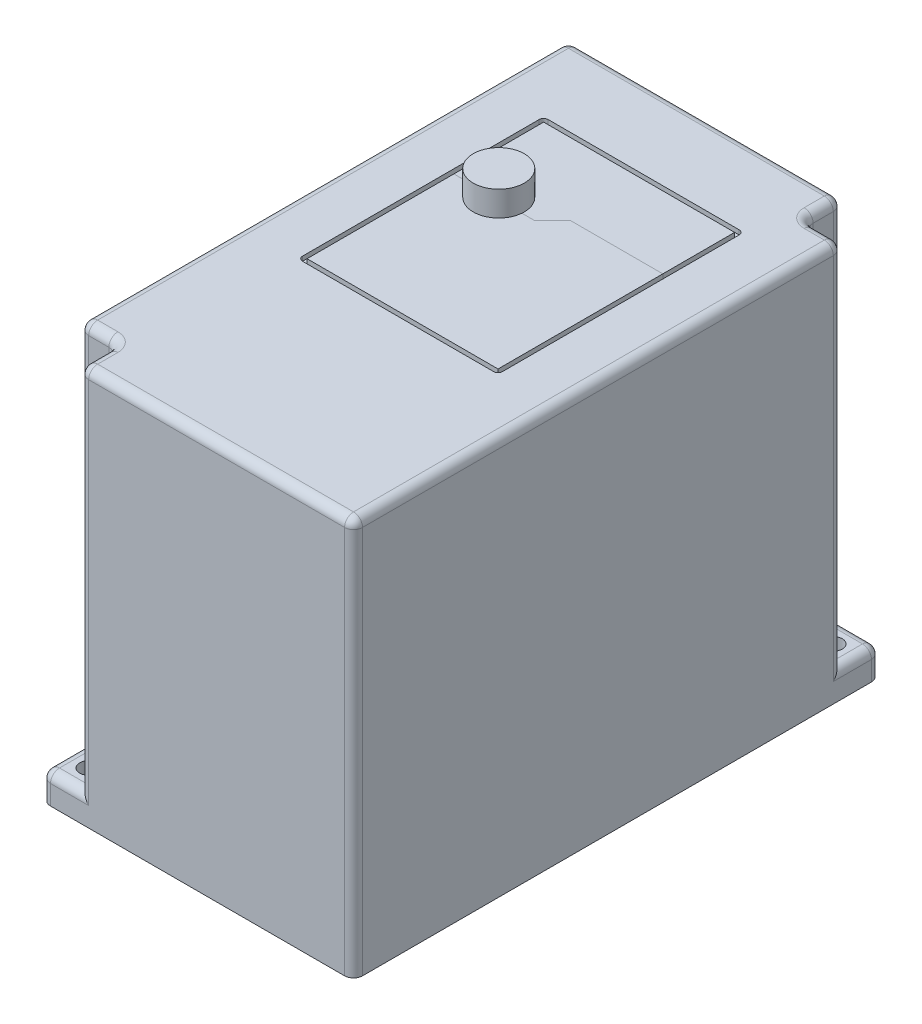
SolidWorks part; units mm, degrees
ref_plane "Front Plane" through (0, 0, 0) normal (0, 0, 1) x (1, 0, 0)
ref_plane "Top Plane" through (0, 0, 0) normal (0, 1, 0) x (1, 0, 0)
ref_plane "Right Plane" through (0, 0, 0) normal (1, 0, 0) x (0, 0, -1)
sketch "Sketch1" plane through (0, 0, 0) normal (0, 1, 0) x (1, 0, 0)
  line L1 (-44.1325, -74.5236) -> (44.1325, -74.5236)
  line L2 (-44.1325, -74.5236) -> (-44.1325, 74.5236)
  line L3 (-44.1325, 74.5236) -> (44.1325, 74.5236)
  line L4 (44.1325, -74.5236) -> (44.1325, 74.5236)
  line L5 (-44.1325, -74.5236) -> (44.1325, 74.5236) construction
  line L6 (-44.1325, 74.5236) -> (44.1325, -74.5236) construction
  point P0 (0, 0)
  dimension "D1" = 149.0472
  dimension "D2" = 88.265
extrude "Boss-Extrude1" add sketch "Sketch1" along normal blind 112.395
sketch "Sketch2" plane through (0, 112.395, 0) normal (0, 1, 0) x (1, 0, 0)
  line L1 (-44.1325, -74.5236) -> (-33.3375, -74.5236)
  line L2 (-44.1325, -74.5236) -> (-44.1325, -63.7286)
  line L3 (-44.1325, -63.7286) -> (-33.3375, -63.7286)
  line L4 (-33.3375, -74.5236) -> (-33.3375, -63.7286)
  line L5 (44.1325, 74.5236) -> (33.3375, 74.5236)
  line L6 (44.1325, 74.5236) -> (44.1325, 63.7286)
  line L7 (44.1325, 63.7286) -> (33.3375, 63.7286)
  line L8 (33.3375, 74.5236) -> (33.3375, 63.7286)
  dimension "D1" = 10.795
  dimension "D2" = 10.795
extrude "Cut-Extrude1" cut sketch "Sketch2" against normal offset from surface (104.3305 mm away) 8.0645 up to face at (0, 0, 0)
sketch "Sketch3" plane through (0, 112.395, 0) normal (0, 1, 0) x (1, 0, 0)
  line L0 (-44.1325, 74.5236) -> (-44.1325, -63.7286) construction
  line L1 (-27.0129, 51.6636) -> (27.0129, 51.6636)
  line L2 (-28.2829, 50.3936) -> (-28.2829, -16.5354)
  line L3 (-27.0129, -17.8054) -> (27.0129, -17.8054)
  line L4 (28.2829, 50.3936) -> (28.2829, -16.5354)
  line L5 (44.1325, -74.5236) -> (44.1325, 63.7286) construction
  line L6 (33.3375, 74.5236) -> (-44.1325, 74.5236) construction
  line L7 (-27.0129, 50.3936) -> (27.0129, 50.3936)
  line L8 (27.0129, 50.3936) -> (27.0129, -16.5354)
  line L9 (-27.0129, -16.5354) -> (27.0129, -16.5354)
  line L10 (-27.0129, 50.3936) -> (-27.0129, -16.5354)
  arc A0 (27.0129, 51.6636) -> (28.2829, 50.3936) centre (27.0129, 50.3936) cw
  arc A1 (27.0129, -17.8054) -> (28.2829, -16.5354) centre (27.0129, -16.5354) ccw
  arc A2 (-28.2829, -16.5354) -> (-27.0129, -17.8054) centre (-27.0129, -16.5354) ccw
  arc A3 (-27.0129, 51.6636) -> (-28.2829, 50.3936) centre (-27.0129, 50.3936) ccw
  arc A4 (27.0129, 50.3936) -> (27.0129, 50.3936) centre (27.0129, 50.3936) cw
  arc A5 (27.0129, -16.5354) -> (27.0129, -16.5354) centre (27.0129, -16.5354) ccw
  arc A6 (-27.0129, -16.5354) -> (-27.0129, -16.5354) centre (-27.0129, -16.5354) ccw
  arc A7 (-27.0129, 50.3936) -> (-27.0129, 50.3936) centre (-27.0129, 50.3936) ccw
  dimension "D5" = 1.27
  dimension "D1" = 15.8496
  dimension "D2" = 15.8496
  dimension "D3" = 22.86
  dimension "D4" = 69.469
  dimension "D6" = 1.27
extrude "Cut-Extrude2" cut sketch "Sketch3" against normal blind 1.27 contours L1 A3 L2 A2 L3 A1 L4 A0 L10 L7 L8 L9
sketch "Sketch4" plane through (0, 112.395, 0) normal (0, 1, 0) x (1, 0, 0)
  line L0 (-27.0129, 50.3936) -> (-27.0129, -16.5354) construction
  line L1 (-27.0129, 50.3936) -> (27.0129, 50.3936) construction
  circle A0 centre (-14.3129, 24.9936) radius 7.2136
  circle A1 centre (-14.3129, 24.9936) radius 5.08
  dimension "D1" = 14.4272
  dimension "D4" = 10.16
  dimension "D2" = 12.7
  dimension "D3" = 25.4
extrude "Boss-Extrude2" add sketch "Sketch4" along normal blind 7.7089 contours A1 | A0 A1
sketch "Sketch7" plane through (0, 120.1039, 0) normal (0, 1, 0) x (1, 0, 0)
  circle A0 centre (-14.3129, 24.9936) radius 5.08
  circle A1 centre (-14.3129, 24.9936) radius 7.2136
  circle A2 centre (-14.3129, 24.9936) radius 7.2136
  circle M2 centre (-14.3129, 24.9936) radius 7.2136
  dimension "D2" = 10.16
  dimension "D1" = 0
extrude "Cut-Extrude5" cut sketch "Sketch7" along normal blind 0.635 from surface at -7.7089 contours A0 M2 starting at face at (-14.3129, 112.395, -32.2072)
fillet "Fillet1" radius 2.54 22 edges at (-5.3975, 112.395, -74.5236) (33.3375, 112.395, -69.1261) (38.735, 112.395, -63.7286) (44.1325, 112.395, 5.3975) (5.3975, 112.395, 74.5236) (-33.3375, 112.395, 69.1261) (-38.735, 112.395, 63.7286) (-44.1325, 112.395, -5.3975) (-44.1325, 60.2297, 63.7286) (-44.1325, 56.1975, -74.5236) (33.3375, 60.2297, -74.5236) (33.3375, 60.2297, -63.7286) (44.1325, 60.2297, -63.7286) (-33.3375, 60.2297, 74.5236) (-33.3375, 60.2297, 63.7286) (44.1325, 56.1975, 74.5236) (-44.1325, 4.0323, 74.5236) (44.1325, 8.0645, -69.1261) (38.735, 8.0645, -74.5236) (-44.1325, 8.0645, 69.1261) (-38.735, 8.0645, 74.5236) (44.1325, 4.0323, -74.5236)
sketch "Sketch8" plane through (0, 112.395, 0) normal (0, 1, 0) x (1, 0, 0)
  line L0 (-14.3129, 24.9936) -> (-27.0129, 24.9936)
  line L1 (-27.0129, 50.3936) -> (-27.0129, -16.5354) construction
  line L2 (-27.0129, 24.9936) -> (-27.0129, 50.3936)
  line L3 (-27.0129, 50.3936) -> (27.0129, 50.3936)
  line L4 (-14.3129, 24.9936) -> (-4.1529, 24.9936)
  line L5 (-4.1529, 24.9936) -> (0.9271, 30.0736)
  line L6 (0.9271, 30.0736) -> (27.0129, 30.0736)
  line L7 (27.0129, 50.3936) -> (27.0129, -16.5354) construction
  line L8 (27.0129, 30.0736) -> (27.0129, 50.3936)
  point P5 (0, 0)
  dimension "D1" = 45
  dimension "D2" = 10.16
  dimension "D3" = 5.08
extrude "Cut-Extrude6" cut sketch "Sketch8" against normal blind 2.54
sketch "Sketch9" plane through (0, 109.855, 0) normal (0, 1, 0) x (1, 0, 0)
  line L6 (-27.0129, 24.9936) -> (-4.1529, 24.9936)
  line L7 (-4.1529, 24.9936) -> (0.9271, 30.0736)
  line L8 (0.9271, 30.0736) -> (27.0129, 30.0736)
  line L9 (27.0129, 30.0736) -> (27.0129, 50.3936)
  line L10 (27.0129, 50.3936) -> (-27.0129, 50.3936)
  line L11 (-27.0129, 50.3936) -> (-27.0129, 24.9936)
  line L12 (-27.0129, 24.9936) -> (-4.1529, 24.9936)
  line L13 (-4.1529, 24.9936) -> (0.9271, 30.0736)
  line L14 (0.9271, 30.0736) -> (27.0129, 30.0736)
  line L15 (27.0129, 30.0736) -> (27.0129, 50.3936)
  line L16 (27.0129, 50.3936) -> (-27.0129, 50.3936)
  line L17 (-27.0129, 50.3936) -> (-27.0129, 24.9936)
  dimension "D1" = 0
extrude "Boss-Extrude3" add sketch "Sketch9" along normal blind 2.54 separate body
sketch "Sketch10" plane through (0, 8.0645, 0) normal (0, 1, 0) x (1, 0, 0)
  line L0 (-41.5925, -63.7286) -> (-41.5925, -71.9836) construction
  line L1 (-33.3375, -71.9836) -> (-33.3375, -66.2686) construction
  line L2 (-41.5925, -71.9836) -> (-33.3375, -71.9836) construction
  line L3 (41.5925, 63.7286) -> (41.5925, 71.9836) construction
  line L4 (41.5925, 71.9836) -> (33.3375, 71.9836) construction
  line L5 (33.3375, 71.9836) -> (33.3375, 66.2686) construction
  circle A0 centre (-37.465, -67.8561) radius 2.54
  circle A1 centre (-37.465, -67.8561) radius 4.1275 construction
  circle A2 centre (37.465, 67.8561) radius 4.1275 construction
  circle A3 centre (37.465, 67.8561) radius 2.54
  dimension "D1" = 5.08
extrude "Cut-Extrude7" cut sketch "Sketch10" against normal through all
